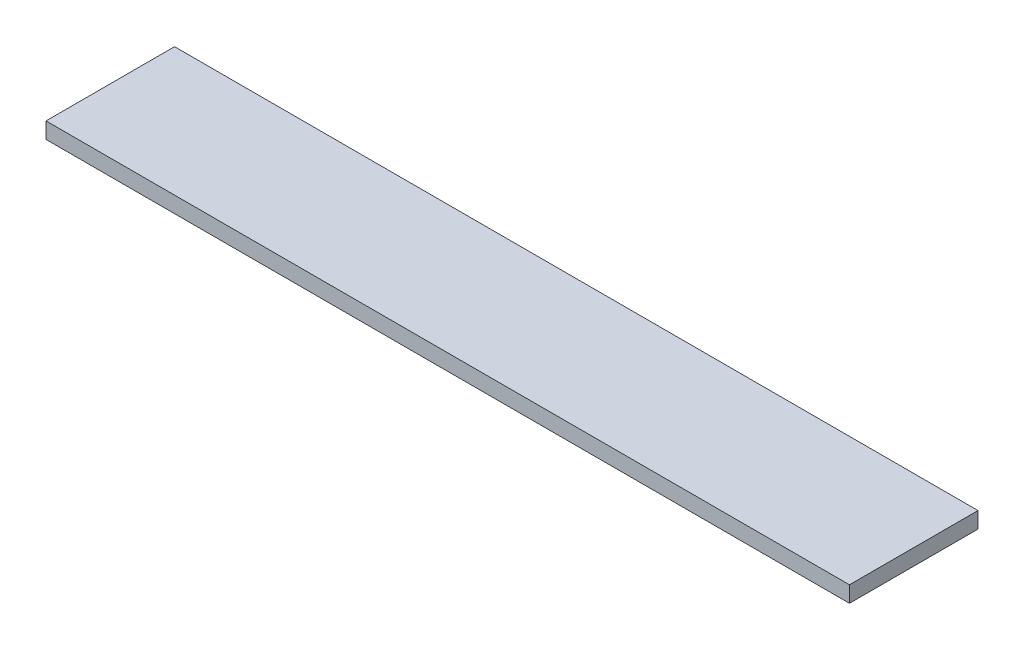
SolidWorks part; units mm, degrees
ref_plane "Front Plane" through (0, 0, 0) normal (0, 0, 1) x (1, 0, 0)
ref_plane "Top Plane" through (0, 0, 0) normal (0, 1, 0) x (1, 0, 0)
ref_plane "Right Plane" through (0, 0, 0) normal (1, 0, 0) x (0, 0, -1)
sketch "Sketch1" plane through (0, 0, 0) normal (0, 1, 0) x (1, 0, 0)
  line L1 (-317.5, -50.8) -> (317.5, -50.8)
  line L2 (-317.5, -50.8) -> (-317.5, 50.8)
  line L3 (-317.5, 50.8) -> (317.5, 50.8)
  line L4 (317.5, -50.8) -> (317.5, 50.8)
  line L5 (-317.5, -50.8) -> (317.5, 50.8) construction
  line L6 (-317.5, 50.8) -> (317.5, -50.8) construction
  point P0 (0, 0)
  dimension "D1" = 101.6
  dimension "D2" = 635
extrude "Boss-Extrude1" add sketch "Sketch1" along normal blind 12.7
